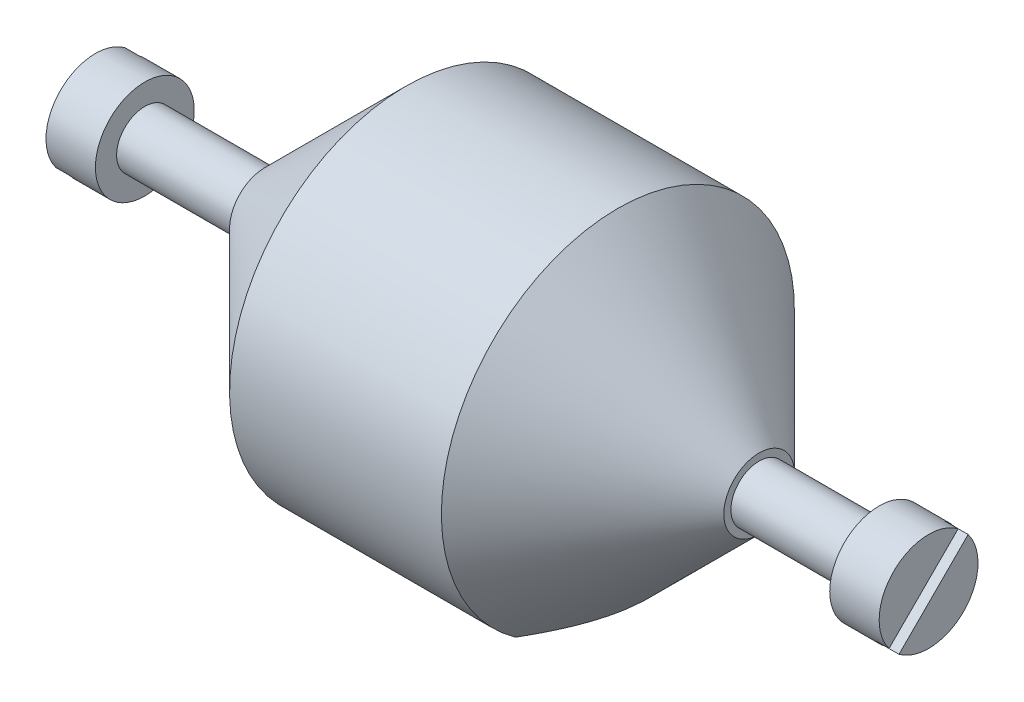
SolidWorks part; units mm, degrees
ref_plane "Front Plane" through (0, 0, 0) normal (0, 0, 1) x (1, 0, 0)
ref_plane "Top Plane" through (0, 0, 0) normal (0, 1, 0) x (1, 0, 0)
ref_plane "Right Plane" through (0, 0, 0) normal (1, 0, 0) x (0, 0, -1)
sketch "Sketch1" plane through (0, 0, 0) normal (1, 0, 0) x (0, 0, -1)
  circle A0 centre (0, 0) radius 12.5
  dimension "D1" = 25
extrude "Boss-Extrude1" add sketch "Sketch1" along normal mid plane 35
sketch "Sketch2" plane through (0, 0, 0) normal (1, 0, 0) x (0, 0, -1)
  circle A0 centre (0, 0) radius 2
  dimension "D1" = 4
extrude "Boss-Extrude2" add sketch "Sketch2" along normal mid plane 52
chamfer "Chamfer1" distance 10 angle 45 2 edges at (-17.5, 0, -12.5) (17.5, 0, -12.5)
sketch "Sketch3" plane through (0, 0, 0) normal (1, 0, 0) x (0, 0, -1)
  line L1 (-13.8538, -10.172) -> (15.1435, -10.172)
  line L2 (-13.8538, -10.172) -> (-13.8538, -17.3693)
  line L3 (-13.8538, -17.3693) -> (15.1435, -17.3693)
  line L4 (15.1435, -10.172) -> (15.1435, -17.3693)
extrude "Cut-Extrude1" cut sketch "Sketch3" against normal mid plane 40
sketch "Sketch4" plane through (0, -10.172, 0) normal (0, -1, 0) x (1, 0, 0)
  circle A0 centre (0, 0) radius 5
extrude "Cut-Extrude2" cut sketch "Sketch4" against normal blind 5
sketch "Sketch5" plane through (-26, 0, 0) normal (-1, 0, 0) x (0, 0, 1)
  circle A0 centre (0, 0) radius 3.5
  dimension "D1" = 7
extrude "Boss-Extrude3" add sketch "Sketch5" along normal blind 3.5
sketch "Sketch6" plane through (-29.5, 0, 0) normal (-1, 0, 0) x (0, 0, 1)
  line L0 (-3.9341, 4.6412) -> (5.6307, -4.9235)
  line L1 (-4.6412, 3.9341) -> (4.9235, -5.6307)
  line L2 (-4.6412, 3.9341) -> (-3.9341, 4.6412)
  line L3 (4.9235, -5.6307) -> (5.8052, -4.749)
  circle M3 centre (0, 0) radius 3.5
  dimension "D2" = 0.5
  dimension "D1" = 1
extrude "Cut-Extrude6" cut sketch "Sketch6" against normal blind 1 contours L1 L0 M3
mirror "Mirror1" about plane through (0, 0, 0) normal (1, 0, 0) of "Cut-Extrude6", "Boss-Extrude3"
